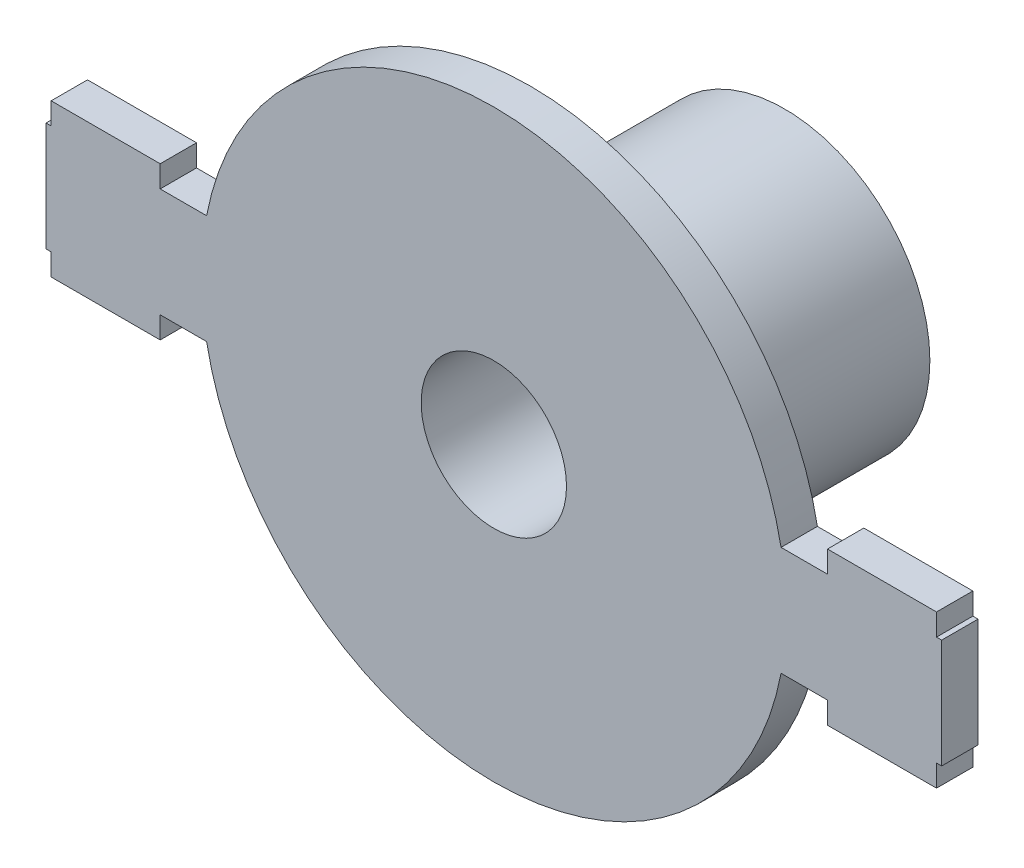
SolidWorks part; units mm, degrees
ref_plane "Ön Düzlem" through (0, 0, 0) normal (0, 0, 1) x (1, 0, 0)
ref_plane "Üst Düzlem" through (0, 0, 0) normal (0, 1, 0) x (1, 0, 0)
ref_plane "Sağ Düzlem" through (0, 0, 0) normal (1, 0, 0) x (0, 0, -1)
sketch "Çizim1" plane through (0, 0, 0) normal (0, 0, 1) x (1, 0, 0)
  circle A0 centre (0, 0) radius 40.225
  dimension "D1" = 80.45
extrude "Yükseklik-Ekstrüzyon1" add sketch "Çizim1" along normal blind 5
sketch "Çizim2" plane through (0, 0, 0) normal (1, 0, 0) x (0, 0, -1)
  line L0 (-5, 40.225) -> (-5, -40.225) construction
  line L1 (-5, 7.5) -> (0, 7.5)
  line L2 (-5, 7.5) -> (-5, -7.5)
  line L3 (-5, -7.5) -> (0, -7.5)
  line L4 (0, 7.5) -> (0, -7.5)
  line L5 (0, -40.225) -> (0, 40.225) construction
  dimension "D1" = 7.5
  dimension "D2" = 7.5
  dimension "D3" = 5
extrude "Yükseklik-Ekstrüzyon2" add sketch "Çizim2" along normal mid plane 128
sketch "Çizim3" plane through (0, -7.5, 0) normal (0, -1, 0) x (1, 0, 0)
  line L0 (-39.5196, 5) -> (-64, 5) construction
  line L1 (-44.5196, 5) -> (-54.5196, 5)
  line L2 (-44.5196, 5) -> (-44.5196, 0)
  line L3 (-44.5196, 0) -> (-54.5196, 0)
  line L4 (-54.5196, 5) -> (-54.5196, 0)
  line L5 (-39.5196, 0) -> (-64, 0) construction
  line L6 (-39.5196, 0) -> (-39.5196, 5) construction
  line L9 (-55.5196, 5) -> (-64, 5)
  line L10 (-55.5196, 5) -> (-55.5196, 0)
  line L11 (-55.5196, 0) -> (-64, 0)
  line L12 (-64, 5) -> (-64, 0)
  dimension "D1" = 5
  dimension "D2" = 5
  dimension "D3" = 10
  dimension "D4" = 1
extrude "Kes-Ekstrüzyon1" cut sketch "Çizim3" against normal blind 128 contours L10 L9 L12 L11
ref_plane "Düzlem1" through (0, 0, 25) normal (0, 0, 1) x (1, 0, 0)
sketch "Çizim6" plane through (0, 0, 25) normal (0, 0, 1) x (1, 0, 0)
  circle A0 centre (0, 0) radius 25
  dimension "D1" = 50
extrude "Yükseklik-Ekstrüzyon4" add sketch "Çizim6" along normal blind 5 separate body
sketch "Çizim7" plane through (0, 0, 5) normal (0, 0, 1) x (1, 0, 0)
  line L0 (35.025, -17.3349) -> (30.6949, -14.8349)
  line L1 (-2.5, 39) -> (2.5, 39)
  line L2 (-2.5, 39) -> (-2.5, 34)
  line L3 (-2.5, 34) -> (2.5, 34)
  line L4 (2.5, 39) -> (2.5, 34)
  line L5 (35.025, -17.3349) -> (32.525, -21.6651)
  line L6 (32.525, -21.6651) -> (28.1949, -19.1651)
  line L7 (30.6949, -14.8349) -> (28.1949, -19.1651)
  line L8 (-32.525, -21.6651) -> (-28.1949, -19.1651)
  line L9 (-32.525, -21.6651) -> (-35.025, -17.3349)
  line L10 (-35.025, -17.3349) -> (-30.6949, -14.8349)
  line L11 (-28.1949, -19.1651) -> (-30.6949, -14.8349)
  arc A0 (39.5196, 7.5) -> (-39.5196, 7.5) centre (0, 0) ccw construction
  point P18 (0, 0)
  dimension "D1" = 2.5
  dimension "D2" = 2.5
  dimension "D3" = 5
  dimension "D4" = 39
  dimension "D5" = 3
extrude "Yükseklik-Ekstrüzyon5" add sketch "Çizim7" along normal blind 2
sketch "Çizim8" plane through (0, 0, 30) normal (0, 0, 1) x (1, 0, 0)
  line L0 (22.0346, -9.8349) -> (17.7045, -7.3349)
  line L1 (-2.5, 24) -> (2.5, 24)
  line L2 (-2.5, 24) -> (-2.5, 19)
  line L3 (-2.5, 19) -> (2.5, 19)
  line L4 (2.5, 24) -> (2.5, 19)
  line L5 (22.0346, -9.8349) -> (19.5346, -14.1651)
  line L6 (19.5346, -14.1651) -> (15.2045, -11.6651)
  line L7 (17.7045, -7.3349) -> (15.2045, -11.6651)
  line L8 (-19.5346, -14.1651) -> (-15.2045, -11.6651)
  line L9 (-19.5346, -14.1651) -> (-22.0346, -9.8349)
  line L10 (-22.0346, -9.8349) -> (-17.7045, -7.3349)
  line L11 (-15.2045, -11.6651) -> (-17.7045, -7.3349)
  point P15 (0, 0)
  dimension "D1" = 2.5
  dimension "D2" = 2.5
  dimension "D3" = 5
  dimension "D4" = 19
  dimension "D5" = 3
extrude "Yükseklik-Ekstrüzyon6" add sketch "Çizim8" against normal blind 7
loft "Loft1" add section face at (-18.6195, -10.75, 23) section face at (-31.6099, -18.25, 7)
loft "Loft3" add section face at (0, 36.5, 7) section face at (0, 21.5, 23)
sketch "Çizim9" plane through (0, -7.5, 0) normal (0, -1, 0) x (1, 0, 0)
  line L10 (64, 5) -> (39.5196, 5) construction
  line L11 (44.5196, 5) -> (59.5196, 5)
  line L12 (44.5196, 5) -> (44.5196, 0)
  line L13 (44.5196, 0) -> (59.5196, 0)
  line L14 (59.5196, 5) -> (59.5196, 0)
  line L15 (64, 0) -> (39.5196, 0) construction
  line L17 (60.2296, 6.5595) -> (65.5694, 6.5595)
  line L18 (60.2296, 6.5595) -> (60.2296, -2.4038)
  line L19 (60.2296, -2.4038) -> (65.5694, -2.4038)
  line L20 (65.5694, 6.5595) -> (65.5694, -2.4038)
  dimension "D1" = 5
  dimension "D2" = 15
  dimension "D3" = 0.71
extrude "Kes-Ekstrüzyon2" cut sketch "Çizim9" against normal blind 23 contours L18 L17 L20 L19
sketch "Çizim10" plane through (0, -7.5, 0) normal (0, -1, 0) x (1, 0, 0)
  line L0 (-39.5196, 5) -> (-55.5196, 5) construction
  line L1 (-44.5196, 5) -> (-61.2296, 5)
  line L2 (-44.5196, 5) -> (-44.5196, 0)
  line L3 (-44.5196, 0) -> (-61.2296, 0)
  line L4 (-61.2296, 5) -> (-61.2296, 0)
  line L5 (-39.5196, 0) -> (-55.5196, 0) construction
  dimension "D1" = 5
  dimension "D2" = 16.71
  dimension "D3" = 5
extrude "Yükseklik-Ekstrüzyon7" add sketch "Çizim10" against normal blind 15
sketch "Çizim11" plane through (0, -7.5, 0) normal (0, -1, 0) x (1, 0, 0)
  line L0 (60.2296, 5) -> (39.5196, 5) construction
  line L1 (45.9096, 5) -> (61.6196, 5)
  line L2 (45.9096, 5) -> (45.9096, 0)
  line L3 (45.9096, 0) -> (61.6196, 0)
  line L4 (61.6196, 5) -> (61.6196, 0)
  line L5 (60.2296, 0) -> (39.5196, 0) construction
  dimension "D1" = 6.39
  dimension "D2" = 15.71
sketch "Çizim13" plane through (0, -7.5, 0) normal (0, -1, 0) x (1, 0, 0)
  line L0 (-39.5196, 5) -> (-61.2296, 5) construction
  line L1 (-45.9096, 5) -> (-60.9096, 5)
  line L2 (-45.9096, 5) -> (-45.9096, 0)
  line L3 (-45.9096, 0) -> (-60.9096, 0)
  line L4 (-60.9096, 5) -> (-60.9096, 0)
  line L5 (-39.5196, 0) -> (-61.2296, 0) construction
  line L7 (-60.9096, 5) -> (-61.6196, 5)
  line L8 (-60.9096, 5) -> (-60.9096, 0)
  line L9 (-60.9096, 0) -> (-61.6196, 0)
  line L10 (-61.6196, 5) -> (-61.6196, 0)
  line M8 (-61.2296, 5) -> (-61.2296, 0)
  dimension "D1" = 5
  dimension "D2" = 6.39
  dimension "D3" = 15
  dimension "D4" = 0.71
extrude "Yükseklik-Ekstrüzyon9" add sketch "Çizim13" against normal blind 15 contours L7 L10 L9 M8
sketch "Çizim14" plane through (0, -7.5, 0) normal (0, -1, 0) x (1, 0, 0)
  line L0 (-39.5196, 5) -> (-61.6196, 5) construction
  line L1 (-45.9096, 5) -> (-60.9096, 5)
  line L2 (-45.9096, 5) -> (-45.9096, 0)
  line L3 (-45.9096, 0) -> (-60.9096, 0)
  line L4 (-60.9096, 5) -> (-60.9096, 0)
  line L5 (-39.5196, 0) -> (-61.6196, 0) construction
  dimension "D1" = 6.39
  dimension "D2" = 15
  dimension "D3" = 0.71
extrude "Yükseklik-Ekstrüzyon10" add sketch "Çizim14" along normal blind 3 and the other way blind 18
extrude "Yükseklik-Ekstrüzyon11" add sketch "Çizim11" against normal blind 15 contours L2 L1 L4 L3
sketch "Çizim16" plane through (0, -7.5, 0) normal (0, -1, 0) x (1, 0, 0)
  line L0 (61.6196, 5) -> (39.5196, 5) construction
  line L1 (45.9096, 5) -> (60.9096, 5)
  line L2 (45.9096, 5) -> (45.9096, 0)
  line L3 (45.9096, 0) -> (60.9096, 0)
  line L4 (60.9096, 5) -> (60.9096, 0)
  line L5 (61.6196, 0) -> (39.5196, 0) construction
  dimension "D1" = 6.39
  dimension "D2" = 15
  dimension "D3" = 0.71
extrude "Yükseklik-Ekstrüzyon12" add sketch "Çizim16" along normal blind 3 and the other way blind 18
sketch "Çizim17" plane through (0, 0, 0) normal (0, 1, 0) x (1, 0, 0)
  line L0 (-45.9096, -5) -> (-60.9096, -5) construction
  line L1 (-53.4096, -5) -> (66.719, -5)
  line L2 (-53.4096, -5) -> (-53.4096, -32.6201)
  line L3 (-53.4096, -32.6201) -> (66.719, -32.6201)
  line L4 (66.719, -5) -> (66.719, -32.6201)
extrude "Kes-Ekstrüzyon3" cut sketch "Çizim17" against normal mid plane 100
sketch "Çizim18" plane through (0, 0, 0) normal (0, 0, -1) x (-1, 0, 0)
  circle A0 centre (0, 0) radius 5
  dimension "D1" = 10
extrude "Kes-Ekstrüzyon4" cut sketch "Çizim18" against normal blind 100
sketch "Çizim20" plane through (0, 0, 0) normal (0, 0, -1) x (-1, 0, 0)
  circle A0 centre (0, 0) radius 20
  circle A1 centre (0, 0) radius 10
  dimension "D1" = 20
extrude "Yükseklik-Ekstrüzyon14" add sketch "Çizim20" along normal blind 35
sketch "Çizim21" plane through (0, 0, 0) normal (0, 0, -1) x (-1, 0, 0)
  circle A0 centre (0, 0) radius 10
extrude "Kes-Ekstrüzyon5" cut sketch "Çizim21" against normal blind 45
